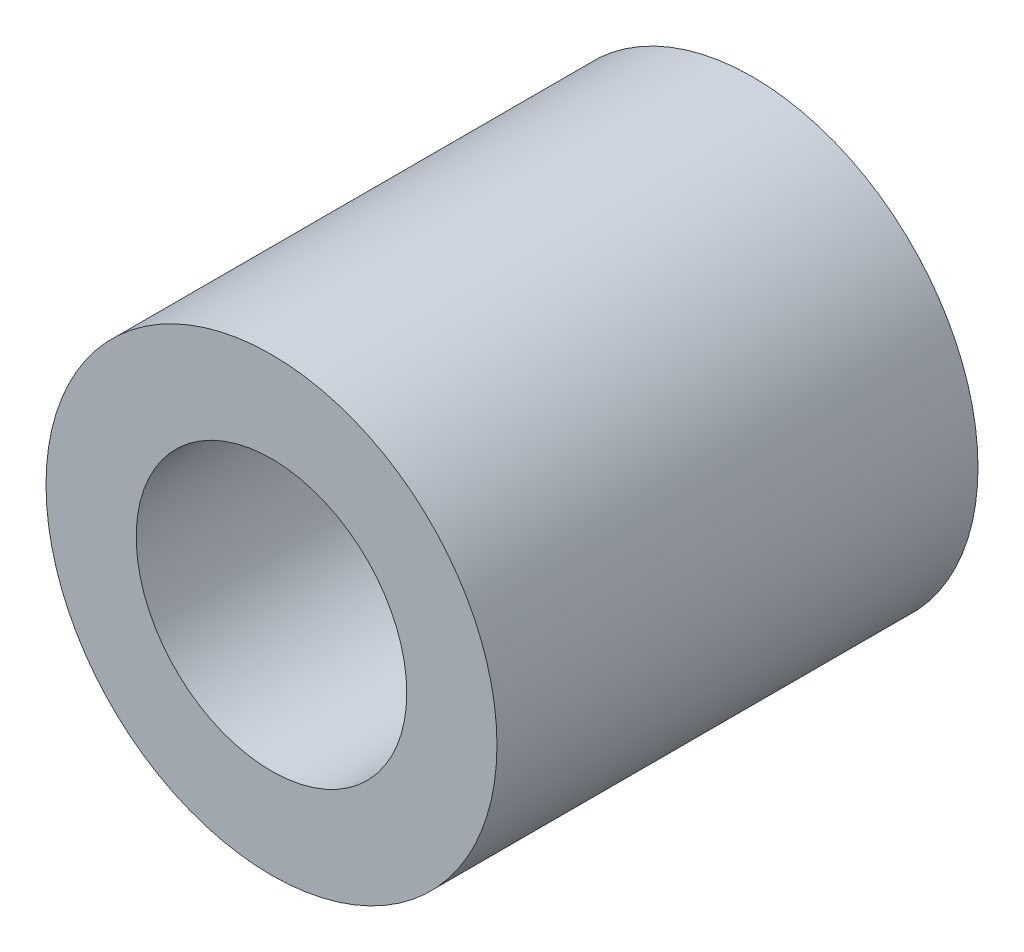
SolidWorks part; units mm, degrees
ref_plane "前视基准面" through (0, 0, 0) normal (0, 0, 1) x (1, 0, 0)
ref_plane "上视基准面" through (0, 0, 0) normal (0, 1, 0) x (1, 0, 0)
ref_plane "右视基准面" through (0, 0, 0) normal (1, 0, 0) x (0, 0, -1)
sketch "草图1" plane through (0, 0, 0) normal (0, 0, 1) x (1, 0, 0)
  circle A0 centre (0, 0) radius 4.5
  circle A1 centre (0, 0) radius 7.5
extrude "凸台-拉伸1" add sketch "草图1" along normal mid plane 16
